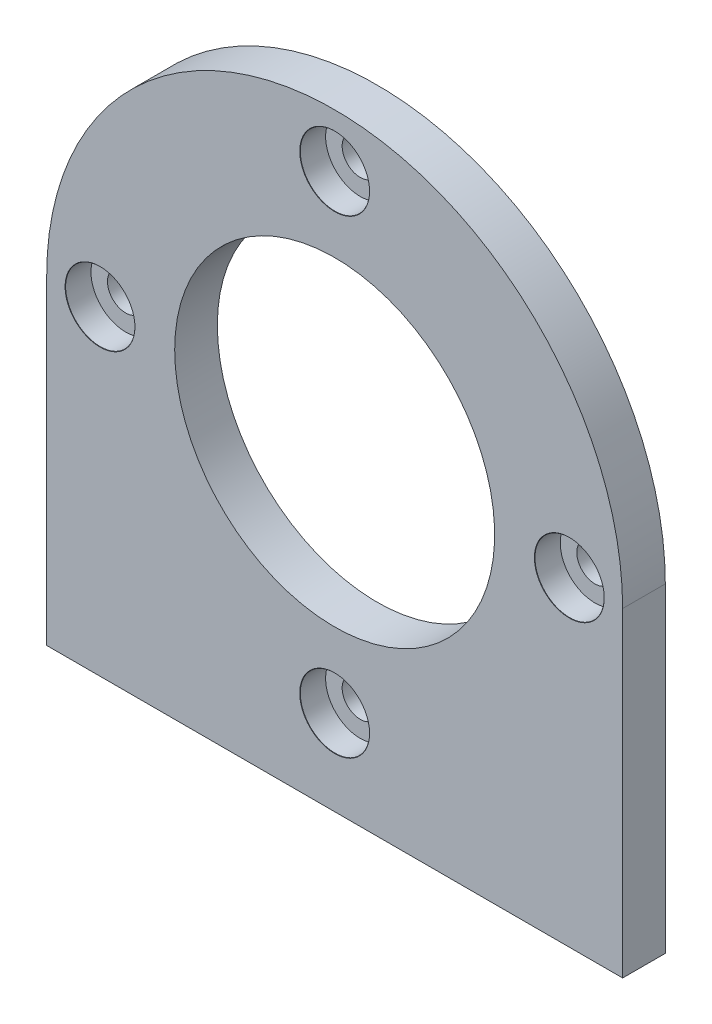
SolidWorks part; units mm, degrees
ref_plane "Front Plane" through (0, 0, 0) normal (0, 0, 1) x (1, 0, 0)
ref_plane "Top Plane" through (0, 0, 0) normal (0, 1, 0) x (1, 0, 0)
ref_plane "Right Plane" through (0, 0, 0) normal (1, 0, 0) x (0, 0, -1)
sketch "Sketch1" plane through (0, 0, 0) normal (0, 0, 1) x (1, 0, 0)
  circle A0 centre (0, 0) radius 27
  dimension "D1" = 54
extrude "Boss-Extrude1" add sketch "Sketch1" along normal blind 4
sketch "Sketch2" plane through (0, 0, 4) normal (0, 0, 1) x (1, 0, 0)
  circle A0 centre (0, 0) radius 22
  point P4 (0, 22)
  point P10 (22, 0)
  point P11 (0, -22)
  point P12 (-22, 0)
  dimension "D1" = 44
  dimension "D2" = 4
hole_wizard "CBORE for M3 Hex Socket Thin Head Cap Screw1" positions "Sketch2" profile "Sketch3" counterbore size "M3" standard "DIN" end condition through all
sketch "Sketch3" plane through (-22, 0, 4) normal (1, 0, 0) x (0, -1, 0)
  line L0 (0, 0) -> (0, 4)
  line L1 (0, 4) -> (1.7, 4)
  line L3 (1.7, 4) -> (1.7, 2.4)
  line L4 (3.25, 2.4) -> (1.7, 2.4)
  line L5 (3.25, 2.4) -> (3.25, 0.025)
  line L6 (3.25, 0.025) -> (3.275, 0)
  line L7 (3.275, 0) -> (0, 0)
  line L8 (-3.25, 0.025) -> (-3.275, 0) construction
  line L11 (0, -6.35) -> (0, 107.95) construction
  dimension "Thru Hole Dia." = 3.4
  dimension "Thru Hole Depth" = 4
  dimension "C'Bore Dia." = 6.5
  dimension "C'Bore Depth" = 2.4
  dimension "Near C'Sink Dia." = 6.55
  dimension "Near C'Sink Angle" = 90
sketch "Sketch4" plane through (0, 0, 4) normal (0, 0, 1) x (1, 0, 0)
  line L0 (-27, 0) -> (-27, -30)
  line L1 (-27, -30) -> (27, -30)
  line L2 (27, -30) -> (27, 0)
  circle A0 centre (0, 0) radius 27 construction
  arc A1 (-27, 0) -> (27, 0) centre (0, 0) ccw
  dimension "D1" = 30
extrude "Boss-Extrude2" add sketch "Sketch4" against normal up to surface (4 mm away) up to face at (1.7, 22, 0)
sketch "Sketch5" plane through (0, 0, 0) normal (0, 0, -1) x (-1, 0, 0)
  circle A0 centre (0, 0) radius 15
  dimension "D1" = 30
extrude "Cut-Extrude1" cut sketch "Sketch5" against normal through all
